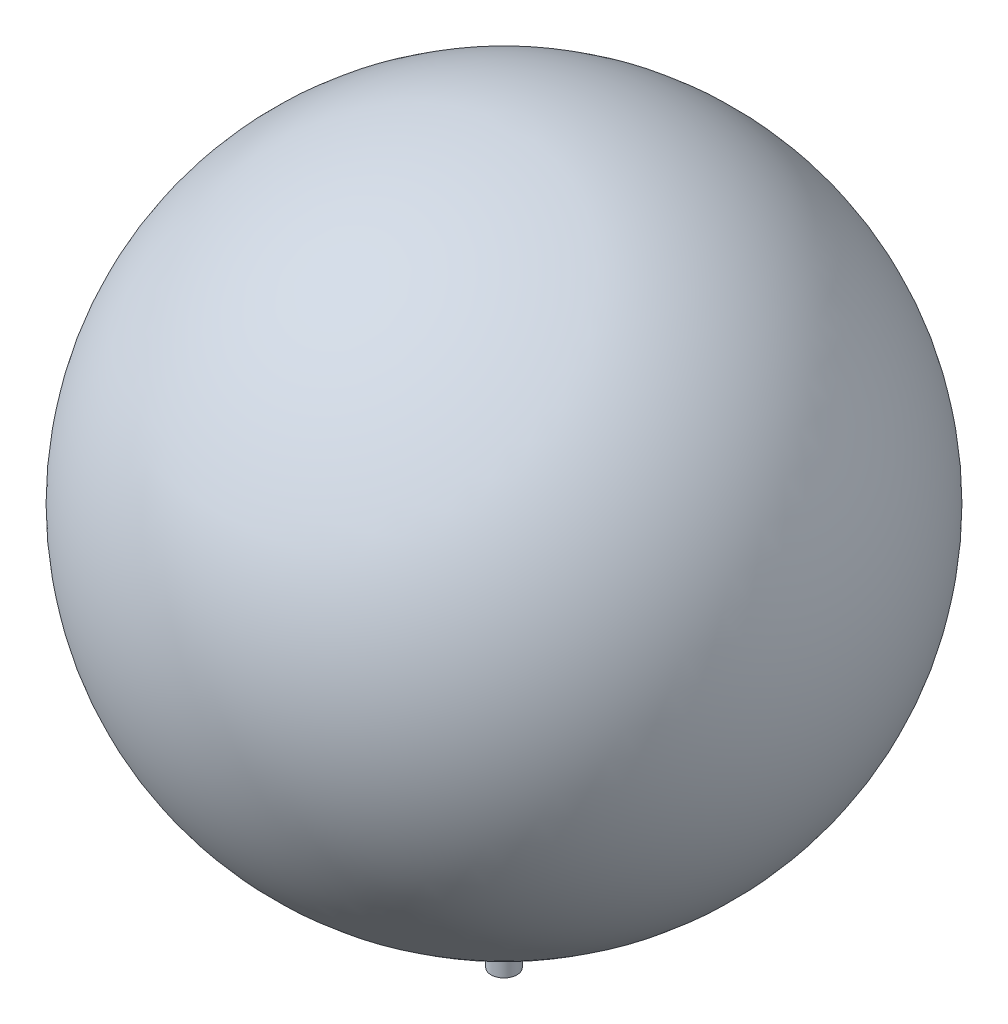
SolidWorks part; units mm, degrees
ref_plane "Front Plane" through (0, 0, 0) normal (0, 0, 1) x (1, 0, 0)
ref_plane "Top Plane" through (0, 0, 0) normal (0, 1, 0) x (1, 0, 0)
ref_plane "Right Plane" through (0, 0, 0) normal (1, 0, 0) x (0, 0, -1)
sketch "Sketch1" plane through (0, 0, 0) normal (0, 0, 1) x (1, 0, 0)
  line L0 (0, 0) -> (0, 50)
  arc A0 (0, 50) -> (0, 0) centre (0, 25) cw
  dimension "D1" = 50
revolve "Revolve1" add sketch "Sketch1" angle 360 about L0
sketch "Sketch2" plane through (0, 0, 0) normal (0, 1, 0) x (1, 0, 0)
  circle A0 centre (0, 0) radius 1
extrude "Boss-Extrude1" add sketch "Sketch2" against normal blind 6 separate body
